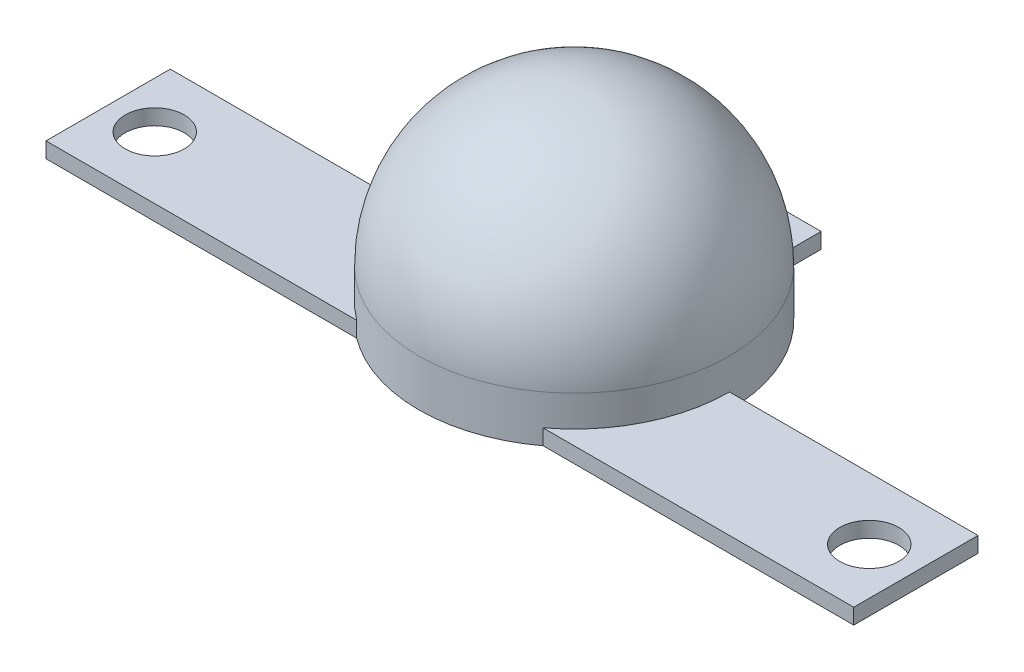
SolidWorks part; units mm, degrees
ref_plane "Спереди" through (0, 0, 0) normal (0, 0, 1) x (1, 0, 0)
ref_plane "Сверху" through (0, 0, 0) normal (0, 1, 0) x (1, 0, 0)
ref_plane "Справа" through (0, 0, 0) normal (1, 0, 0) x (0, 0, -1)
other "Configuration Table"
sketch "Эскиз1" plane through (0, 0, 0) normal (0, 0, 1) x (1, 0, 0)
  line L0 (8.8, 0) -> (10, 0)
  line L2 (10, 0) -> (10, 3)
  line L3 (8.8, 0) -> (8.8, 3)
  line L4 (0, 13) -> (0, 11.8)
  line L6 (0, 13) -> (0, 0) construction
  arc A1 (10, 3) -> (0, 13) centre (0, 3) ccw
  arc A2 (0, 11.8) -> (8.8, 3) centre (0, 3) cw
  dimension "D1" = 1.2
  dimension "D2" = 10
  dimension "D3" = 3
revolve "Повернуть1" add sketch "Эскиз1" angle 360 about L6
sketch "Эскиз2" plane through (0, 0, 0) normal (0, 1, 0) x (1, 0, 0)
  line L0 (26, 0) -> (-26, 0)
  line L1 (26, -8) -> (-26, -8)
  line L2 (0, 0) -> (0, -8) construction
  line L3 (-26, -8) -> (-26, 0)
  line L4 (26, -8) -> (26, 0)
  line L5 (-4, 0) -> (-4, 11.9)
  line L6 (4, 0) -> (4, 11.9)
  line L7 (4, 11.9) -> (-4, 11.9)
  circle A0 centre (-23, -4) radius 1.9
  circle A1 centre (23, -4) radius 1.9
  point P4 (0, 0)
  point P9 (0, -8)
  point P11 (0, -4)
  dimension "D2" = 3.8
  dimension "D3" = 52
  dimension "D1" = 23
  dimension "D4" = 8
  dimension "D5" = 4
  dimension "D6" = 11.9
extrude "Бобышка-Вытянуть1" add sketch "Эскиз2" along normal blind 1 contours L2 L0 L3 L1 A0 | L0 L2 L1 L4 A1 | L6 L7 L5 L0
